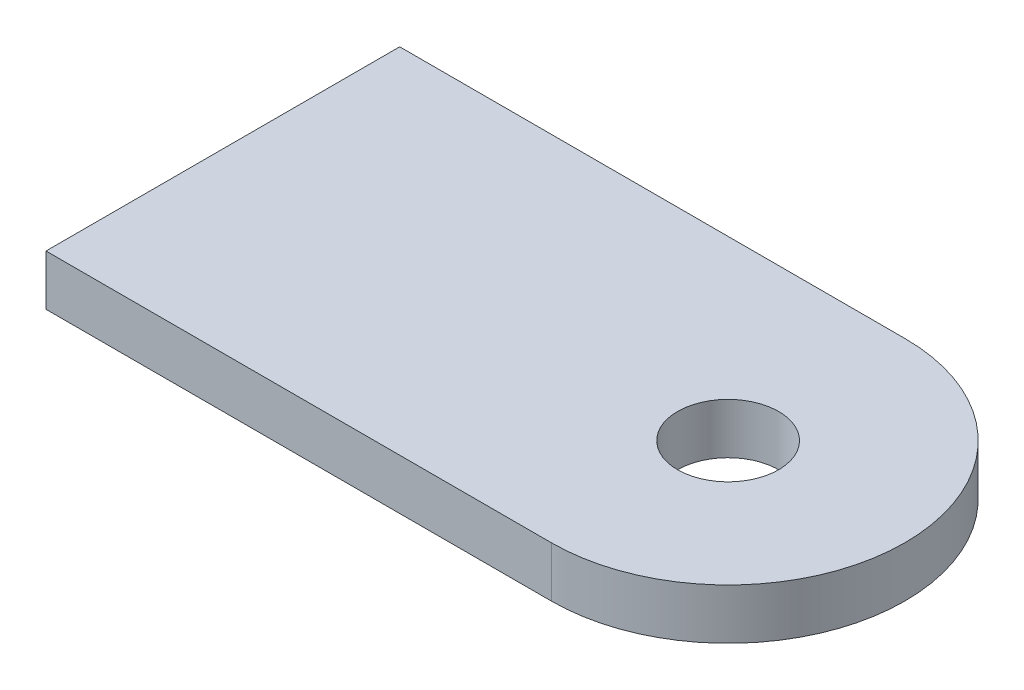
SolidWorks part; units mm, degrees
ref_plane "Front Plane" through (0, 0, 0) normal (0, 0, 1) x (1, 0, 0)
ref_plane "Top Plane" through (0, 0, 0) normal (0, 1, 0) x (1, 0, 0)
ref_plane "Right Plane" through (0, 0, 0) normal (1, 0, 0) x (0, 0, -1)
sketch "Sketch1" plane through (0, 0, 0) normal (0, 1, 0) x (1, 0, 0)
  line L0 (0, 0) -> (0, 0.7)
  line L1 (0, 0.7) -> (1, 0.7)
  line L2 (0, 0) -> (1, 0)
  arc A0 (1, 0.7) -> (1, 0) centre (1, 0.35) cw
  circle A1 centre (1, 0.35) radius 0.1
  dimension "D3" = 0.2
  dimension "D1" = 0.7
  dimension "D2" = 1
extrude "Boss-Extrude1" add sketch "Sketch1" along normal blind 0.1
